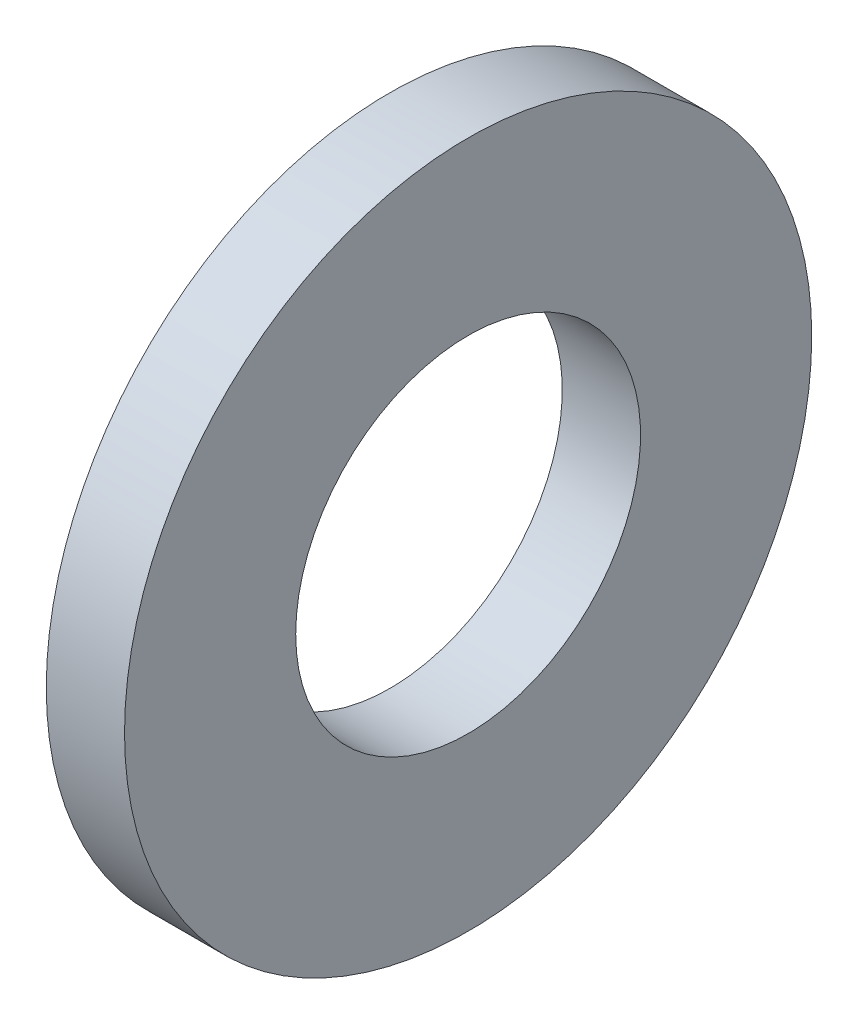
SolidWorks part; units mm, degrees
material "Plain Carbon Steel"
ref_plane "Plane1" through (0, 0, 0) normal (0, 0, 1) x (1, 0, 0)
ref_plane "Plane2" through (0, 0, 0) normal (0, 1, 0) x (1, 0, 0)
ref_plane "Plane3" through (0, 0, 0) normal (1, 0, 0) x (0, 0, -1)
other "Configuration Table"
sketch "Sketch1" plane through (0, 0, 0) normal (0, 0, 1) x (1, 0, 0)
  line L0 (-34.925, 0) -> (9.525, 0) construction
  line L1 (0, 1.7907) -> (0, 3.5687)
  line L2 (0, 3.5687) -> (-0.8128, 3.5687)
  line L3 (-0.8128, 3.5687) -> (-0.8128, 1.7907)
  line L4 (-0.8128, 1.7907) -> (0, 1.7907)
  dimension "Thickness" = 0.8128
  dimension "Inside_dia" = 3.5814
  dimension "Outside_dia" = 7.1374
revolve "Base-Revolve" add sketch "Sketch1" angle 360 about L0
